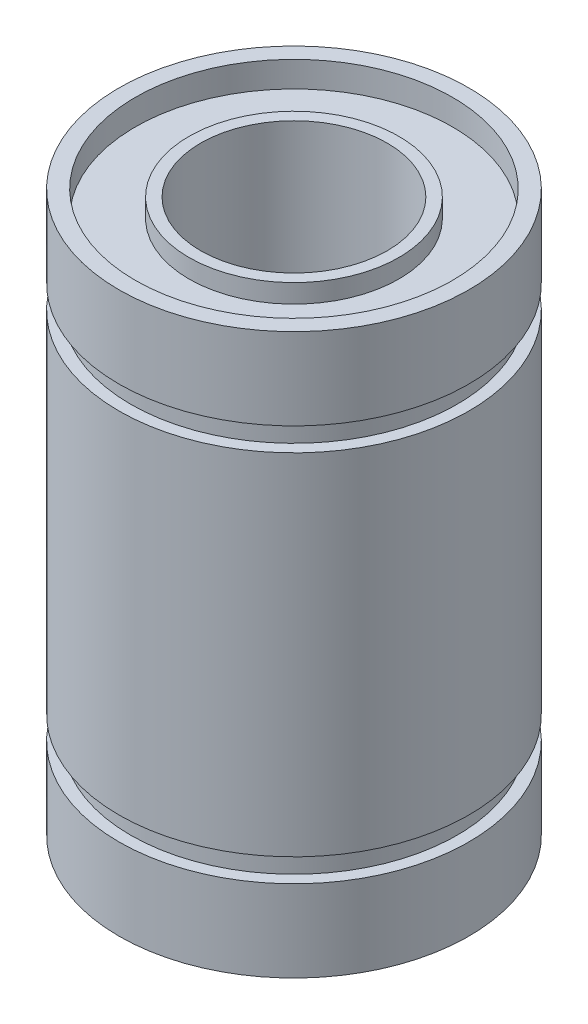
SolidWorks part; units mm, degrees
material "Chrome Stainless Steel"
ref_plane "Front Plane" through (0, 0, 0) normal (0, 0, 1) x (1, 0, 0)
ref_plane "Top Plane" through (0, 0, 0) normal (0, 1, 0) x (1, 0, 0)
ref_plane "Right Plane" through (0, 0, 0) normal (1, 0, 0) x (0, 0, -1)
sketch "Sketch1" plane through (0, 0, 0) normal (0, 1, 0) x (1, 0, 0)
  circle A0 centre (0, 0) radius 7.5
  dimension "D1" = 15
extrude "Boss-Extrude1" add sketch "Sketch1" along normal mid plane 24
sketch "Sketch2" plane through (0, 12, 0) normal (0, 1, 0) x (1, 0, 0)
  circle A0 centre (0, 0) radius 4
  dimension "D1" = 8
extrude "Cut-Extrude1" cut sketch "Sketch2" against normal blind 24
sketch "Sketch3" plane through (0, 12, 0) normal (0, 1, 0) x (1, 0, 0)
  circle A0 centre (0, 0) radius 7
  circle A1 centre (0, 0) radius 7.5
  circle A2 centre (0, 0) radius 7.5
  dimension "D1" = 0
  dimension "D2" = 0.5
extrude "Cut-Extrude2" cut sketch "Sketch3" against normal blind 1 from offset 3.5 offset against normal yes
sketch "Sketch4" plane through (0, 0, 0) normal (1, 0, 0) x (0, 0, -1)
  line L0 (4, 12) -> (4, 11.7)
  line L1 (4, 11.7) -> (4.5, 11.7)
  line L2 (4.5, 11.7) -> (4.5, 10.9)
  line L3 (4.5, 10.9) -> (6.8, 10.9)
  line L4 (6.8, 10.9) -> (6.8, 12)
  line L5 (6.8, 12) -> (4, 12)
  line L6 (0, 10.5) -> (0, -2.243) construction
  dimension "D1" = 0.3
  dimension "D3" = 1.1
  dimension ".8" = 2.8
  dimension "D5" = 0.8
revolve "Cut-Revolve1" cut sketch "Sketch4" angle 360 about L6
mirror "Mirror1" about plane through (0, 0, 0) normal (0, 1, 0) of "Cut-Revolve1", "Cut-Extrude2"
